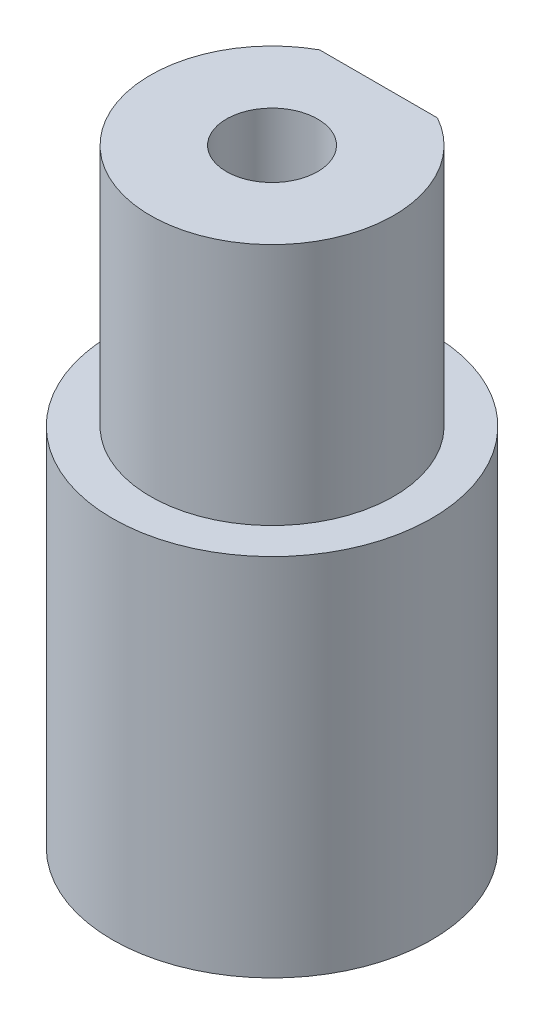
SolidWorks part; units mm, degrees
ref_plane "Front Plane" through (0, 0, 0) normal (0, 0, 1) x (1, 0, 0)
ref_plane "Top Plane" through (0, 0, 0) normal (0, 1, 0) x (1, 0, 0)
ref_plane "Right Plane" through (0, 0, 0) normal (1, 0, 0) x (0, 0, -1)
sketch "Sketch1" plane through (0, 0, 0) normal (0, 1, 0) x (1, 0, 0)
  circle A0 centre (0, 0) radius 5.25
  circle A1 centre (0, 0) radius 3
extrude "Boss-Extrude1" add sketch "Sketch1" along normal blind 12 contours A0
sketch "Sketch2" plane through (0, 12, 0) normal (0, 1, 0) x (1, 0, 0)
  circle A0 centre (0, 0) radius 4
  circle A1 centre (0, 0) radius 1.5
extrude "Boss-Extrude2" add sketch "Sketch2" along normal blind 8 contours A1 | A0
sketch "Sketch4" plane through (0, 20, 0) normal (0, 1, 0) x (1, 0, 0)
  line L2 (-1.9365, 3.5) -> (1.9365, 3.5)
  circle A0 centre (0, 0) radius 4 construction
  arc A2 (1.9365, 3.5) -> (-1.9365, 3.5) centre (0, 0) ccw
extrude "Cut-Extrude2" cut sketch "Sketch4" against normal blind 8 contours L2 A2
